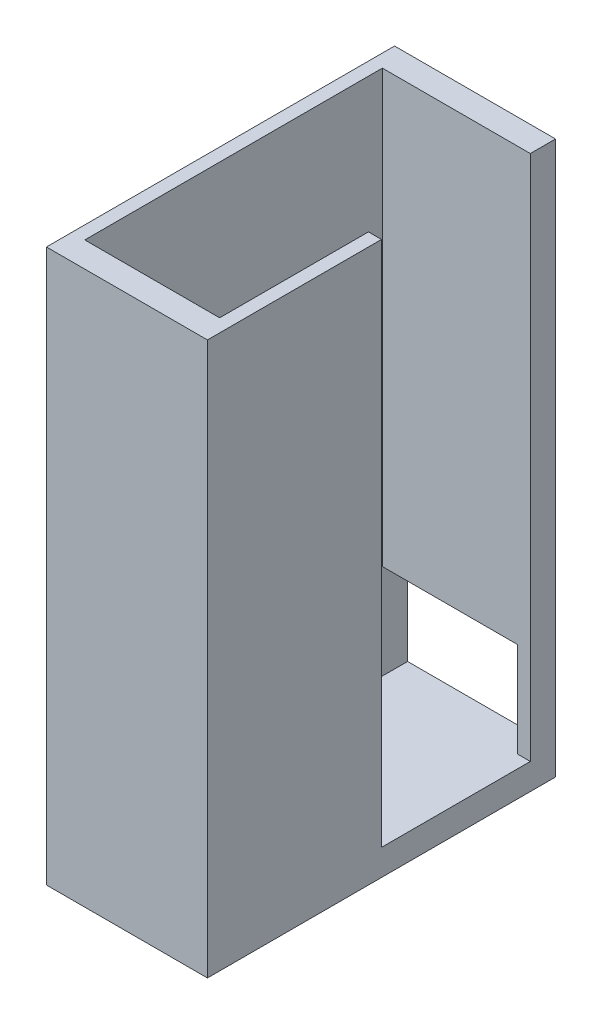
SolidWorks part; units mm, degrees
ref_plane "Front Plane" through (0, 0, 0) normal (0, 0, 1) x (1, 0, 0)
ref_plane "Top Plane" through (0, 0, 0) normal (0, 1, 0) x (1, 0, 0)
ref_plane "Right Plane" through (0, 0, 0) normal (1, 0, 0) x (0, 0, -1)
sketch "Sketch1" plane through (0, 0, 0) normal (0, 1, 0) x (1, 0, 0)
  line L1 (0, 0) -> (18.5, 0)
  line L2 (0, 0) -> (0, 40)
  line L3 (0, 40) -> (18.5, 40)
  line L4 (18.5, 0) -> (18.5, 40)
  dimension "D1" = 18.5
  dimension "D2" = 40
extrude "Boss-Extrude1" add sketch "Sketch1" along normal blind 3
sketch "Sketch2" plane through (0, 3, 0) normal (0, 1, 0) x (1, 0, 0)
  line L0 (0, 40) -> (18.5, 40)
  line L1 (18.5, 40) -> (18.5, 37.1)
  line L2 (18.5, 0) -> (18.5, 40) construction
  line L3 (18.5, 37.1) -> (0, 37.1)
  line L4 (0, 40) -> (0, 0) construction
  line L5 (0, 37.1) -> (0, 40)
  line L6 (0, 37.1) -> (0, 0)
  line L7 (0, 0) -> (1.5, 0)
  line L8 (0, 0) -> (18.5, 0) construction
  line L9 (1.5, 0) -> (1.5, 37.1)
  line L10 (1.5, 37.1) -> (0, 37.1)
  line L11 (1.5, 0) -> (18.5, 0)
  line L12 (18.5, 0) -> (18.5, 2.9)
  line L13 (18.5, 2.9) -> (1.5, 2.9)
  line L14 (1.5, 2.9) -> (1.5, 0)
  line L15 (18.5, 37.1) -> (18.5, 2.9)
  line L16 (18.5, 2.9) -> (17, 2.9)
  line L17 (18.5, 2.9) -> (18.5, 20)
  line L18 (18.5, 20) -> (17, 20)
  line L19 (17, 20) -> (17, 2.9)
  dimension "D1" = 2.9
  dimension "D2" = 2.9
  dimension "D3" = 1.5
  dimension "D4" = 1.5
extrude "Boss-Extrude2" add sketch "Sketch2" along normal blind 60.5 contours L5 L0 L1 L3 | L6 L7 L9 L10 | L17 L18 L19 L16 | L11 L12 L13 L14
sketch "Sketch4" plane through (0, 0, -40) normal (0, 0, -1) x (-1, 0, 0)
  line L0 (-1.5, 3) -> (-17, 3)
  line L1 (-17, 3) -> (-17, 13.9)
  line L2 (-17, 13.9) -> (-1.5, 13.9)
  line L3 (-1.5, 13.9) -> (-1.5, 3)
  line L4 (-18.5, 0) -> (0, 0) construction
  line L5 (0, 63.5) -> (-18.5, 63.5) construction
  line L6 (0, 63.5) -> (0, 0) construction
  line L7 (-18.5, 63.5) -> (-18.5, 0) construction
  dimension "D1" = 3
  dimension "D2" = 49.6
  dimension "D3" = 1.5
  dimension "D4" = 1.5
extrude "Cut-Extrude1" cut sketch "Sketch4" against normal up to next
